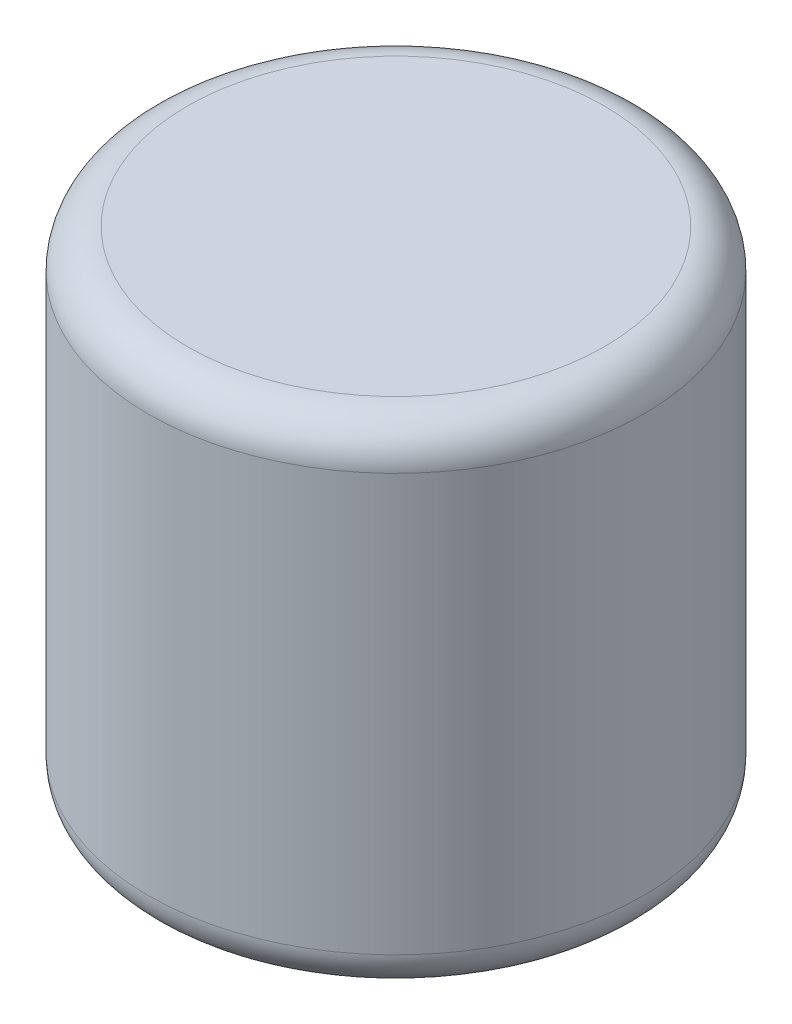
SolidWorks part; units mm, degrees
ref_plane "Front" through (0, 0, 0) normal (0, 0, 1) x (1, 0, 0)
ref_plane "Top" through (0, 0, 0) normal (0, 1, 0) x (1, 0, 0)
ref_plane "Right" through (0, 0, 0) normal (1, 0, 0) x (0, 0, -1)
sketch "Sketch1" plane through (0, 0, 0) normal (0, 1, 0) x (1, 0, 0)
  circle A0 centre (0, 0) radius 3.175
  dimension "D1" = 6.35
extrude "Boss-Extrude1" add sketch "Sketch1" along normal mid plane 6.35
fillet "Fillet1" radius 0.5 2 edges at (0, -3.175, 3.175) (0, 3.175, 3.175)
